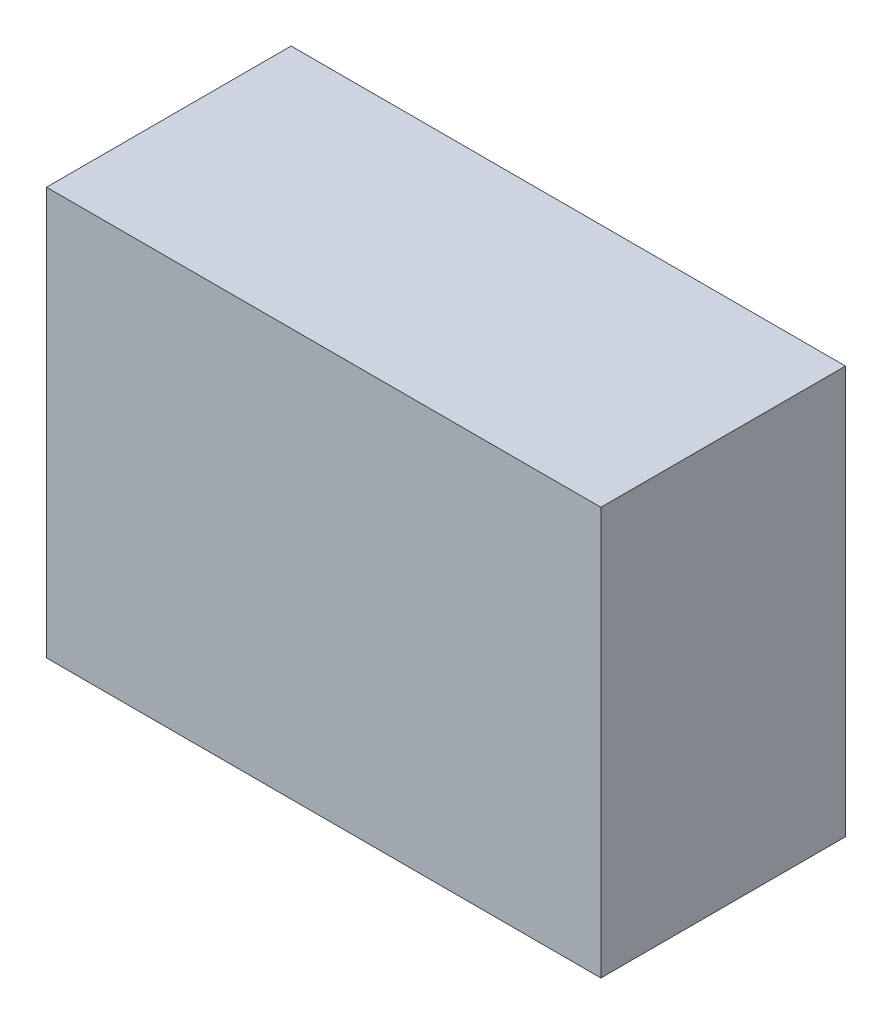
SolidWorks part; units mm, degrees
ref_plane "Front Plane" through (0, 0, 0) normal (0, 0, 1) x (1, 0, 0)
ref_plane "Top Plane" through (0, 0, 0) normal (0, 1, 0) x (1, 0, 0)
ref_plane "Right Plane" through (0, 0, 0) normal (1, 0, 0) x (0, 0, -1)
sketch "Sketch1" plane through (0, 0, 0) normal (0, 0, 1) x (1, 0, 0)
  line L1 (86.36, -63.5) -> (-86.36, -63.5)
  line L2 (86.36, -63.5) -> (86.36, 63.5)
  line L3 (86.36, 63.5) -> (-86.36, 63.5)
  line L4 (-86.36, -63.5) -> (-86.36, 63.5)
  line L5 (86.36, -63.5) -> (-86.36, 63.5) construction
  line L6 (86.36, 63.5) -> (-86.36, -63.5) construction
  point P0 (0, 0)
  dimension "D1" = 172.72
  dimension "D2" = 127
extrude "Boss-Extrude1" add sketch "Sketch1" along normal blind 76.2
